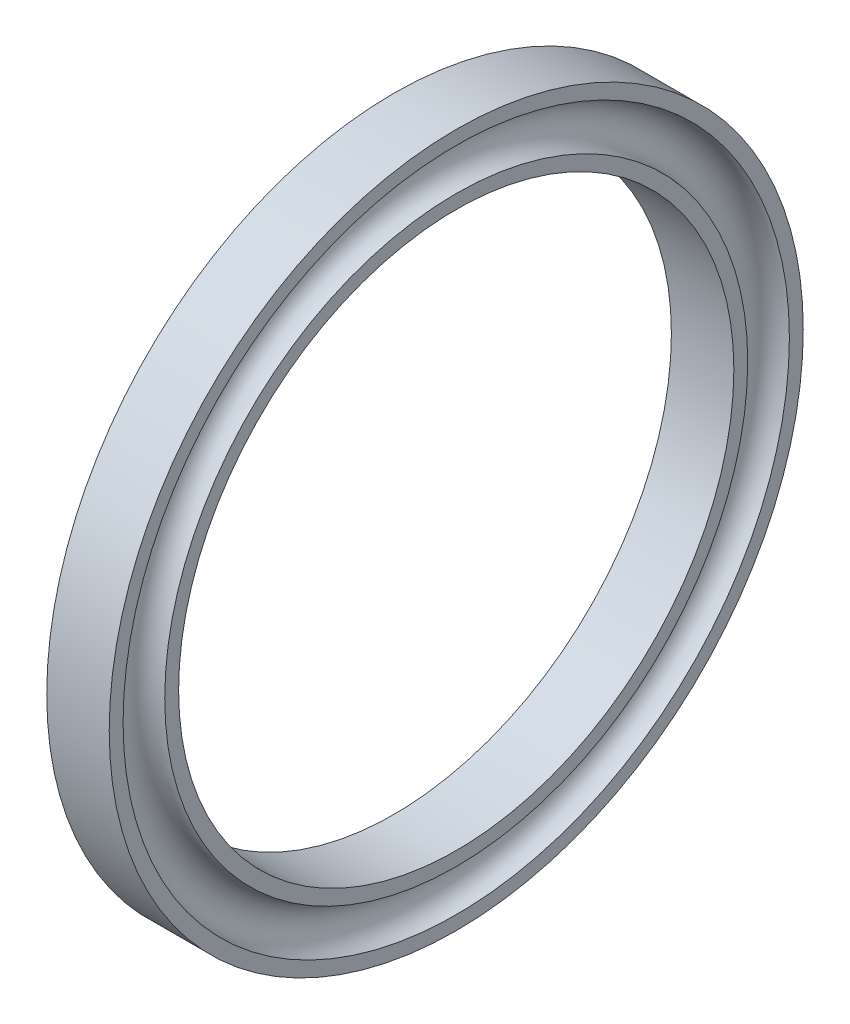
SolidWorks part; units mm, degrees
ref_plane "Płaszczyzna przednia" through (0, 0, 0) normal (0, 0, 1) x (1, 0, 0)
ref_plane "Płaszczyzna górna" through (0, 0, 0) normal (0, 1, 0) x (1, 0, 0)
ref_plane "Płaszczyzna prawa" through (0, 0, 0) normal (1, 0, 0) x (0, 0, -1)
sketch "Szkic1" plane through (0, 0, 0) normal (0, 0, 1) x (1, 0, 0)
  line L0 (-18.0751, -45.8936) -> (-18.0751, -50.8936) construction
  line L1 (-15.8251, -45.8936) -> (-20.3251, -45.8936)
  line L2 (-15.8251, -45.8936) -> (-15.8251, -46.8936)
  line L3 (-15.8251, -50.8936) -> (-20.3251, -50.8936)
  line L4 (-20.3251, -45.8936) -> (-20.3251, -46.8936)
  line L5 (-20.3251, -49.8936) -> (-20.3251, -50.8936)
  line L6 (-15.8251, -49.8936) -> (-15.8251, -50.8936)
  line L7 (19.5311, -70.8936) -> (11.4631, -70.8936) construction
  line L9 (-20.3251, -48.3936) -> (-15.8251, -48.3936) construction
  line L10 (-20.3251, -95.8936) -> (-20.3251, -45.8936) construction
  arc A0 (-20.3251, -46.8936) -> (-20.3251, -49.8936) centre (-20.3251, -48.3936) cw
  arc A1 (-15.8251, -46.8936) -> (-15.8251, -49.8936) centre (-15.8251, -48.3936) ccw
  point P19 (-18.0751, -48.3936)
  dimension "D1" = 1.5
  dimension "D2" = 4.5
  dimension "D3" = 5
  dimension "D4" = 40
revolve "Obrót1" add sketch "Szkic1" angle 360 about L7
